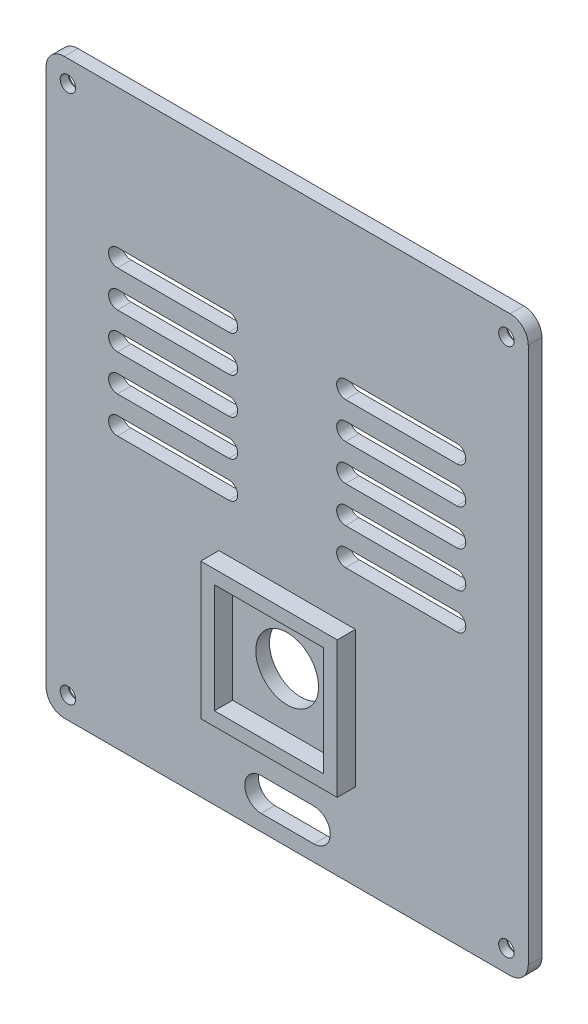
SolidWorks part; units mm, degrees
ref_plane "前视基准面" through (0, 0, 0) normal (0, 0, 1) x (1, 0, 0)
ref_plane "上视基准面" through (0, 0, 0) normal (0, 1, 0) x (1, 0, 0)
ref_plane "右视基准面" through (0, 0, 0) normal (1, 0, 0) x (0, 0, -1)
sketch "草图1" plane through (0, 0, 0) normal (0, 0, 1) x (1, 0, 0)
  line L1 (0, 0) -> (53, 0)
  line L2 (0, 0) -> (0, 63)
  line L3 (0, 63) -> (53, 63)
  line L4 (53, 0) -> (53, 63)
  dimension "D1" = 53
  dimension "D2" = 63
extrude "凸台-拉伸1" add sketch "草图1" along normal blind 1.5
fillet "圆角1" radius 2 4 edges at (53, 63, 0.75) (0, 63, 0.75) (0, 0, 0.75) (53, 0, 0.75)
sketch "草图3" plane through (0, 0, 0) normal (0, 0, -1) x (-1, 0, 0)
  line L2 (-23.6357, 5.35) -> (-29.4357, 5.35)
  line L3 (-29.4357, 1.75) -> (-23.6357, 1.75)
  line L4 (-23.6357, 5.35) -> (-29.4357, 5.35)
  line L5 (-29.4357, 1.75) -> (-23.6357, 1.75)
  arc A2 (-29.4357, 5.35) -> (-29.4357, 1.75) centre (-29.4357, 3.55) ccw
  arc A3 (-23.6357, 1.75) -> (-23.6357, 5.35) centre (-23.6357, 3.55) ccw
  arc A4 (-29.4357, 5.35) -> (-29.4357, 1.75) centre (-29.4357, 3.55) ccw
  arc A5 (-23.6357, 1.75) -> (-23.6357, 5.35) centre (-23.6357, 3.55) ccw
  dimension "D1" = 0
extrude "切除-拉伸2" cut sketch "草图3" against normal through all
sketch "草图4" plane through (0, 0, 1.5) normal (0, 0, 1) x (1, 0, 0)
  line L0 (26.5, 63) -> (26.5, 0) construction
  line L1 (51, 63) -> (2, 63) construction
  line L2 (2, 0) -> (51, 0) construction
  line L3 (7.8403, 46.7582) -> (20.0857, 46.7582) construction
  line L4 (7.8403, 47.7301) -> (20.0857, 47.7301)
  line L5 (7.8403, 45.7863) -> (20.0857, 45.7863)
  line L6 (7.8403, 42.7582) -> (20.0857, 42.7582) construction
  line L7 (7.8403, 43.7301) -> (20.0857, 43.7301)
  line L8 (7.8403, 41.7863) -> (20.0857, 41.7863)
  line L9 (7.8403, 38.7582) -> (20.0857, 38.7582) construction
  line L10 (7.8403, 39.7301) -> (20.0857, 39.7301)
  line L11 (7.8403, 37.7863) -> (20.0857, 37.7863)
  line L12 (7.8403, 34.7582) -> (20.0857, 34.7582) construction
  line L13 (7.8403, 35.7301) -> (20.0857, 35.7301)
  line L14 (7.8403, 33.7863) -> (20.0857, 33.7863)
  line L15 (7.8403, 30.7582) -> (20.0857, 30.7582) construction
  line L16 (7.8403, 31.7301) -> (20.0857, 31.7301)
  line L17 (7.8403, 29.7863) -> (20.0857, 29.7863)
  line L18 (45.1597, 30.7582) -> (32.9143, 30.7582) construction
  line L19 (45.1597, 31.7301) -> (32.9143, 31.7301)
  line L20 (45.1597, 29.7863) -> (32.9143, 29.7863)
  line L21 (45.1597, 34.7582) -> (32.9143, 34.7582) construction
  line L22 (45.1597, 35.7301) -> (32.9143, 35.7301)
  line L23 (45.1597, 33.7863) -> (32.9143, 33.7863)
  line L24 (45.1597, 38.7582) -> (32.9143, 38.7582) construction
  line L25 (45.1597, 39.7301) -> (32.9143, 39.7301)
  line L26 (45.1597, 37.7863) -> (32.9143, 37.7863)
  line L27 (45.1597, 42.7582) -> (32.9143, 42.7582) construction
  line L28 (45.1597, 43.7301) -> (32.9143, 43.7301)
  line L29 (45.1597, 41.7863) -> (32.9143, 41.7863)
  line L30 (45.1597, 46.7582) -> (32.9143, 46.7582) construction
  line L31 (45.1597, 47.7301) -> (32.9143, 47.7301)
  line L32 (45.1597, 45.7863) -> (32.9143, 45.7863)
  arc A0 (7.8403, 47.7301) -> (7.8403, 45.7863) centre (7.8403, 46.7582) ccw
  arc A1 (20.0857, 45.7863) -> (20.0857, 47.7301) centre (20.0857, 46.7582) ccw
  arc A2 (7.8403, 43.7301) -> (7.8403, 41.7863) centre (7.8403, 42.7582) ccw
  arc A3 (20.0857, 41.7863) -> (20.0857, 43.7301) centre (20.0857, 42.7582) ccw
  arc A4 (7.8403, 39.7301) -> (7.8403, 37.7863) centre (7.8403, 38.7582) ccw
  arc A5 (20.0857, 37.7863) -> (20.0857, 39.7301) centre (20.0857, 38.7582) ccw
  arc A6 (7.8403, 35.7301) -> (7.8403, 33.7863) centre (7.8403, 34.7582) ccw
  arc A7 (20.0857, 33.7863) -> (20.0857, 35.7301) centre (20.0857, 34.7582) ccw
  arc A8 (7.8403, 31.7301) -> (7.8403, 29.7863) centre (7.8403, 30.7582) ccw
  arc A9 (20.0857, 29.7863) -> (20.0857, 31.7301) centre (20.0857, 30.7582) ccw
  arc A10 (45.1597, 31.7301) -> (45.1597, 29.7863) centre (45.1597, 30.7582) cw
  arc A11 (32.9143, 29.7863) -> (32.9143, 31.7301) centre (32.9143, 30.7582) cw
  arc A12 (45.1597, 35.7301) -> (45.1597, 33.7863) centre (45.1597, 34.7582) cw
  arc A13 (32.9143, 33.7863) -> (32.9143, 35.7301) centre (32.9143, 34.7582) cw
  arc A14 (45.1597, 39.7301) -> (45.1597, 37.7863) centre (45.1597, 38.7582) cw
  arc A15 (32.9143, 37.7863) -> (32.9143, 39.7301) centre (32.9143, 38.7582) cw
  arc A16 (45.1597, 43.7301) -> (45.1597, 41.7863) centre (45.1597, 42.7582) cw
  arc A17 (32.9143, 41.7863) -> (32.9143, 43.7301) centre (32.9143, 42.7582) cw
  arc A18 (45.1597, 47.7301) -> (45.1597, 45.7863) centre (45.1597, 46.7582) cw
  arc A19 (32.9143, 45.7863) -> (32.9143, 47.7301) centre (32.9143, 46.7582) cw
  point P8 (13.963, 46.7582)
  point P17 (13.963, 42.7582)
  point P24 (13.963, 38.7582)
  point P31 (13.963, 34.7582)
  point P38 (13.963, 30.7582)
  point P45 (39.037, 30.7582)
  point P52 (39.037, 34.7582)
  point P59 (39.037, 38.7582)
  point P66 (39.037, 42.7582)
  point P73 (39.037, 46.7582)
  dimension "D1" = 5
extrude "切除-拉伸3" cut sketch "草图4" against normal through all
sketch "草图5" plane through (0, 0, 1.5) normal (0, 0, 1) x (1, 0, 0)
  line L0 (26.5, 63) -> (26.5, 0) construction
  line L1 (51, 63) -> (2, 63) construction
  line L2 (2, 0) -> (51, 0) construction
  circle A0 centre (26.5, 16.9545) radius 3.45
  dimension "D1" = 6.9
extrude "切除-拉伸4" cut sketch "草图5" against normal through all
sketch "草图6" plane through (0, 0, 1.5) normal (0, 0, 1) x (1, 0, 0)
  line L1 (32.5, 10.9545) -> (20.5, 10.9545)
  line L2 (32.5, 10.9545) -> (32.5, 22.9545)
  line L3 (32.5, 22.9545) -> (20.5, 22.9545)
  line L4 (20.5, 10.9545) -> (20.5, 22.9545)
  line L5 (32.5, 10.9545) -> (20.5, 22.9545) construction
  line L6 (32.5, 22.9545) -> (20.5, 10.9545) construction
  point P0 (26.5, 16.9545)
  dimension "D1" = 12
  dimension "D2" = 12
extrude "拉伸-薄壁1" add sketch "草图6" along normal blind 2 thin thin type one direction wall 1.5
sketch "草图9" plane through (0, 0, 0) normal (0, 0, -1) x (-1, 0, 0)
  line L0 (-26.5, 63) -> (-26.5, 0) construction
  line L1 (-51, 63) -> (-2, 63) construction
  line L2 (-51.75, 1.4243) -> (-51.75, 61.9243) construction
  line L3 (-51.75, 31.6743) -> (0.75, 31.5) construction
  line L4 (0.75, 61.75) -> (0.75, 1.25) construction
  circle A0 centre (-2.4, 2.4) radius 0.85
  circle A2 centre (-50.6, 60.6) radius 0.85
  circle A3 centre (-2.4, 60.6) radius 0.85
  circle A6 centre (-50.6, 2.4) radius 0.85
  dimension "D1" = 1.7
  dimension "D2" = 1.7
extrude "切除-拉伸5" cut sketch "草图9" against normal through all
sketch "草图10" plane through (0, 0, 0) normal (0, 0, -1) x (-1, 0, 0)
  line L0 (-26.5, 63) -> (-26.5, 0) construction
  line L1 (-51, 63) -> (-2, 63) construction
  line L2 (-52.25, 58.25) -> (-52.25, 4.75) construction
  line L3 (-52.25, 31.5) -> (0, 31.5) construction
  line L4 (0, 61) -> (0, 2) construction
  circle A0 centre (-50.6, 60.6) radius 1.55
  circle A1 centre (-2.4, 60.6) radius 1.55
  circle A2 centre (-2.4, 2.4) radius 1.55
  circle A3 centre (-50.6, 2.4) radius 1.55
  dimension "D1" = 3.1
extrude "切除-拉伸6" cut sketch "草图10" against normal blind 0.6
